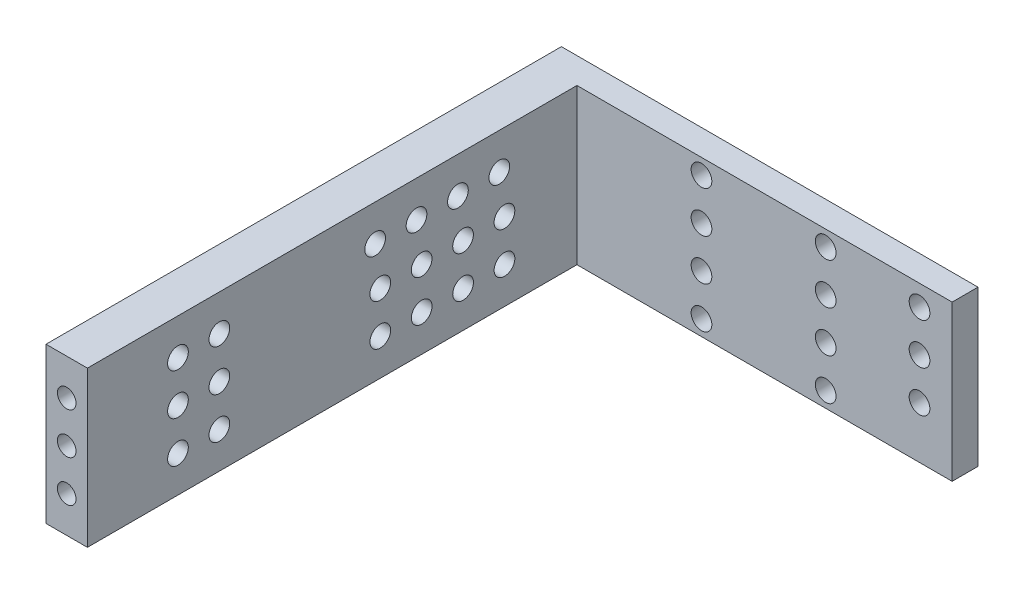
SolidWorks part; units mm, degrees
material "ABS"
ref_plane "前基準面" through (0, 0, 0) normal (0, 0, 1) x (1, 0, 0)
ref_plane "上基準面" through (0, 0, 0) normal (0, 1, 0) x (1, 0, 0)
ref_plane "右基準面" through (0, 0, 0) normal (1, 0, 0) x (0, 0, -1)
sketch "草圖1" plane through (0, 0, 0) normal (0, 1, 0) x (1, 0, 0)
  line L0 (0, 0) -> (0, 107.1)
  line L1 (0, 107.1) -> (80.5, 107.1)
  line L2 (80.5, 107.1) -> (80.5, 102.1)
  line L3 (80.5, 102.1) -> (8, 102.1)
  line L4 (8, 102.1) -> (8, 0)
  line L5 (8, 0) -> (0, 0)
  dimension "D1" = 107.1
  dimension "D2" = 80.5
  dimension "D3" = 72.5
  dimension "D4" = 5
extrude "填料-伸長1" add sketch "草圖1" along normal blind 30
sketch "草圖2" plane through (0, 0, 0) normal (0, 0, 1) x (1, 0, 0)
  line L4 (0, 30) -> (8, 30) construction
  line L6 (8, 30) -> (8, 0) construction
  circle A0 centre (4, 23) radius 1.8
  circle A1 centre (4, 7) radius 1.8
  circle A2 centre (4, 15) radius 1.8
  dimension "D1" = 8
  dimension "D3" = 7
  dimension "D4" = 4
  dimension "D5" = 3.6
  dimension "D2" = 8
sketch "草圖3" plane through (0, 0, 0) normal (-1, 0, 0) x (0, 0, 1)
  line L0 (-107.1, 30) -> (0, 30) construction
  line L2 (0, 30) -> (0, 0) construction
  line L3 (-107.1, 30) -> (-107.1, 0) construction
  circle A0 centre (-25, 23) radius 2
  circle A1 centre (-25, 15) radius 2
  circle A2 centre (-25, 7) radius 2
  circle A3 centre (-33, 23) radius 2
  circle A4 centre (-33, 15) radius 2
  circle A5 centre (-33, 7) radius 2
  circle A9 centre (-63.1, 23) radius 2
  circle A10 centre (-64.0923, 15.0618) radius 2
  circle A11 centre (-64.0999, 7.0618) radius 2
  circle A12 centre (-71.1, 23) radius 2
  circle A13 centre (-72.0923, 15.0618) radius 2
  circle A14 centre (-72.0999, 7.0618) radius 2
  circle A15 centre (-79.1, 23) radius 2
  circle A16 centre (-80.0923, 15.0618) radius 2
  circle A17 centre (-80.0999, 7.0618) radius 2
  circle A18 centre (-87.1, 23) radius 2
  circle A19 centre (-88.0923, 15.0618) radius 2
  circle A20 centre (-88.0999, 7.0618) radius 2
  dimension "D1" = 4
  dimension "D2" = 4
  dimension "D3" = 4
  dimension "D9" = 4
  dimension "D10" = 4
  dimension "D11" = 4
  dimension "D4" = 8
  dimension "D5" = 8
  dimension "D6" = 7
  dimension "D7" = 2
  dimension "D8" = 25
  dimension "D12" = 8
  dimension "D13" = 8
  dimension "D14" = 7
  dimension "D16" = 20
  dimension "D15" = 4
extrude "除料-伸長2" cut sketch "草圖3" against normal blind 10
sketch "草圖4" plane through (0, 0, -107.1) normal (0, 0, -1) x (-1, 0, 0)
  line L0 (-80.5, 30) -> (0, 30) construction
  line L1 (-80.5, 30) -> (-80.5, 0) construction
  circle A0 centre (-74.2, 26) radius 2
  circle A1 centre (-74.2, 18) radius 2
  circle A2 centre (-74.2, 10) radius 2
  dimension "D1" = 4
  dimension "D2" = 4
  dimension "D3" = 4
  dimension "D4" = 8
  dimension "D5" = 8
  dimension "D6" = 4
  dimension "D7" = 6.3
extrude "除料-伸長3" cut sketch "草圖4" against normal blind 10
extrude "除料-伸長4" cut sketch "草圖2" against normal blind 20
sketch "草圖5" plane through (0, 30, 0) normal (0, 1, 0) x (1, 0, 0)
  line L0 (8, 0) -> (8, 102.1) construction
  line L1 (0, 0) -> (8, 0)
  line L2 (0, 0) -> (0, 7.5)
  line L3 (0, 7.5) -> (8, 7.5)
  line L4 (8, 0) -> (8, 7.5)
  dimension "D1" = 7.5
extrude "除料-伸長5" cut sketch "草圖5" against normal up to vertex (30 mm away)
sketch "草圖6" plane through (0, 0, -107.1) normal (0, 0, -1) x (-1, 0, 0)
  line L1 (-80.5, 30) -> (0, 30) construction
  circle A0 centre (-56.0677, 27) radius 2
  circle A1 centre (-56.0677, 19) radius 2
  circle A2 centre (-56.0677, 11) radius 2
  circle A3 centre (-32.0677, 27) radius 2
  circle A4 centre (-32.0677, 19) radius 2
  circle A5 centre (-32.0677, 11) radius 2
  circle A6 centre (-56.0677, 3) radius 2
  circle A7 centre (-32.0677, 3) radius 2
  dimension "D2" = 8
  dimension "D3" = 8
  dimension "D4" = 8
  dimension "D5" = 24
  dimension "D6" = 4
  dimension "D7" = 8
  dimension "D8" = 8
  dimension "D9" = 3
  dimension "D1" = 8
extrude "除料-伸長6" cut sketch "草圖6" against normal blind 10
